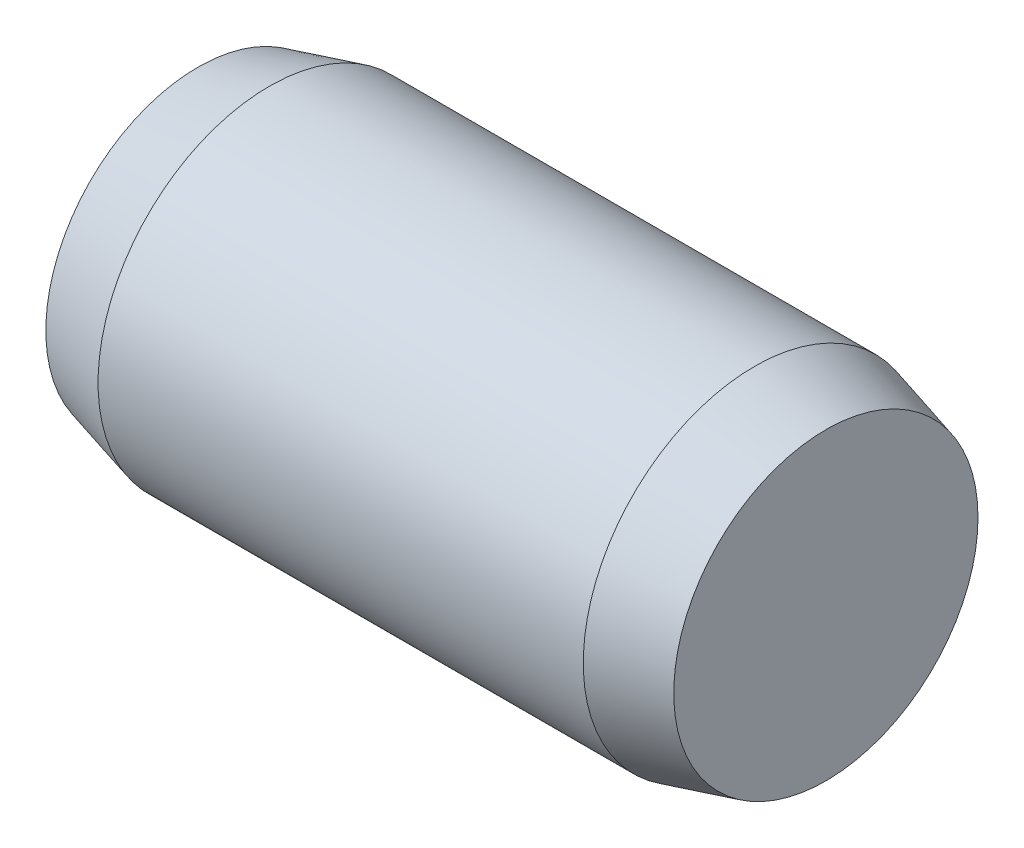
SolidWorks part; units mm, degrees
ref_plane "前视" through (0, 0, 0) normal (0, 0, 1) x (1, 0, 0)
ref_plane "上视" through (0, 0, 0) normal (0, 1, 0) x (1, 0, 0)
ref_plane "右视" through (0, 0, 0) normal (1, 0, 0) x (0, 0, -1)
sketch "草图1" plane through (0, 0, 0) normal (0, 0, 1) x (1, 0, 0)
  line L0 (0, 0) -> (-1.8279, 0) construction
  line L1 (0, 0) -> (22, 0)
  line L2 (2.5, 6) -> (19.5, 6)
  line L3 (22, 5.3301) -> (22, 0)
  line L4 (19.5, 6) -> (22, 5.3301)
  line L5 (2.5, -6) -> (19.5, -6) construction
  line L6 (2.5, 6) -> (0, 5.3301)
  line L7 (0, 5.3301) -> (0, 0)
  point P13 (11, 6)
  dimension "D1" = 165
  dimension "D2" = 2.5
  dimension "D3" = 165
  dimension "c" = 2.5
  dimension "l" = 22
  dimension "d" = 12
revolve "基体-旋转" add sketch "草图1" angle 360 about L0
